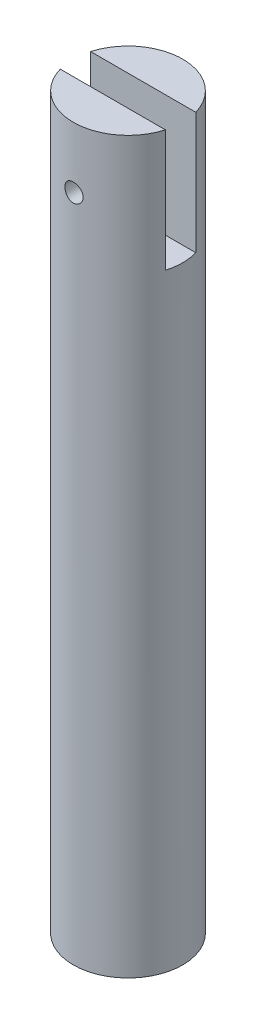
SolidWorks part; units mm, degrees
ref_plane "Front Plane" through (0, 0, 0) normal (0, 0, 1) x (1, 0, 0)
ref_plane "Top Plane" through (0, 0, 0) normal (0, 1, 0) x (1, 0, 0)
ref_plane "Right Plane" through (0, 0, 0) normal (1, 0, 0) x (0, 0, -1)
sketch "Sketch1" plane through (0, 0, 0) normal (0, 1, 0) x (1, 0, 0)
  circle A0 centre (0, 0) radius 18
  dimension "D1" = 36
extrude "Boss-Extrude1" add sketch "Sketch1" along normal mid plane 240
sketch "Sketch2" plane through (0, 120, 0) normal (0, 1, 0) x (1, 0, 0)
  line L1 (-25, 5) -> (25, 5)
  line L2 (-25, 5) -> (-25, -5)
  line L3 (-25, -5) -> (25, -5)
  line L4 (25, 5) -> (25, -5)
  line L5 (-25, 5) -> (25, -5) construction
  line L6 (-25, -5) -> (25, 5) construction
  point P0 (0, 0)
  dimension "D1" = 10
  dimension "D2" = 50
extrude "Cut-Extrude1" cut sketch "Sketch2" against normal blind 40
sketch "Sketch3" plane through (0, 0, 0) normal (0, 0, 1) x (1, 0, 0)
  line L0 (17.2916, 120) -> (-17.2916, 120) construction
  circle A0 centre (0, 100) radius 3
  dimension "D1" = 6
  dimension "D2" = 20
extrude "Cut-Extrude2" cut sketch "Sketch3" against normal through all both and the other way through all
